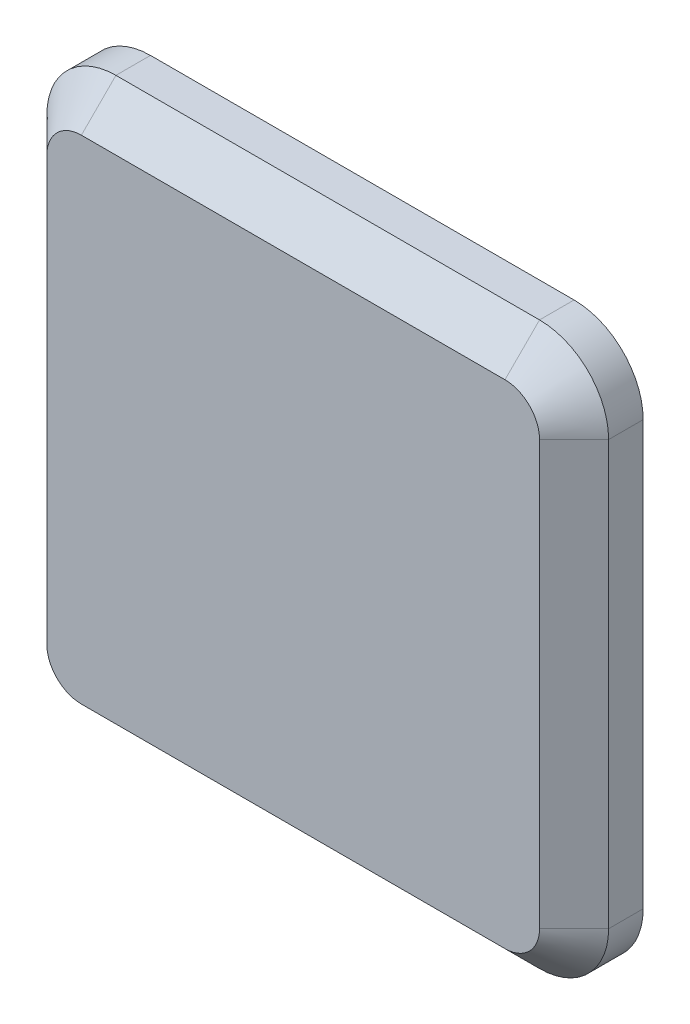
SolidWorks part; units mm, degrees
ref_plane "Front Plane" through (0, 0, 0) normal (0, 0, 1) x (1, 0, 0)
ref_plane "Top Plane" through (0, 0, 0) normal (0, 1, 0) x (1, 0, 0)
ref_plane "Right Plane" through (0, 0, 0) normal (1, 0, 0) x (0, 0, -1)
sketch "Sketch1" plane through (0, 0, 0) normal (0, 0, 1) x (1, 0, 0)
  line L1 (16.2635, -16.2635) -> (-16.2635, -16.2635)
  line L2 (16.2635, -16.2635) -> (16.2635, 16.2635)
  line L3 (16.2635, 16.2635) -> (-16.2635, 16.2635)
  line L4 (-16.2635, -16.2635) -> (-16.2635, 16.2635)
  line L5 (16.2635, -16.2635) -> (-16.2635, 16.2635) construction
  line L6 (16.2635, 16.2635) -> (-16.2635, -16.2635) construction
  point P0 (0, 0)
  dimension "D1" = 46
extrude "Boss-Extrude1" add sketch "Sketch1" along normal blind 4
fillet "Fillet1" radius 4 4 edges at (-16.2635, -16.2635, 2) (16.2635, -16.2635, 2) (16.2635, 16.2635, 2) (-16.2635, 16.2635, 2)
chamfer "Chamfer1" distance 2 angle 45 8 edges at (0, -16.2635, 4) (15.0919, -15.0919, 4) (-15.0919, -15.0919, 4) (16.2635, 0, 4) (-16.2635, 0, 4) (15.0919, 15.0919, 4) (-15.0919, 15.0919, 4) (0, 16.2635, 4)
